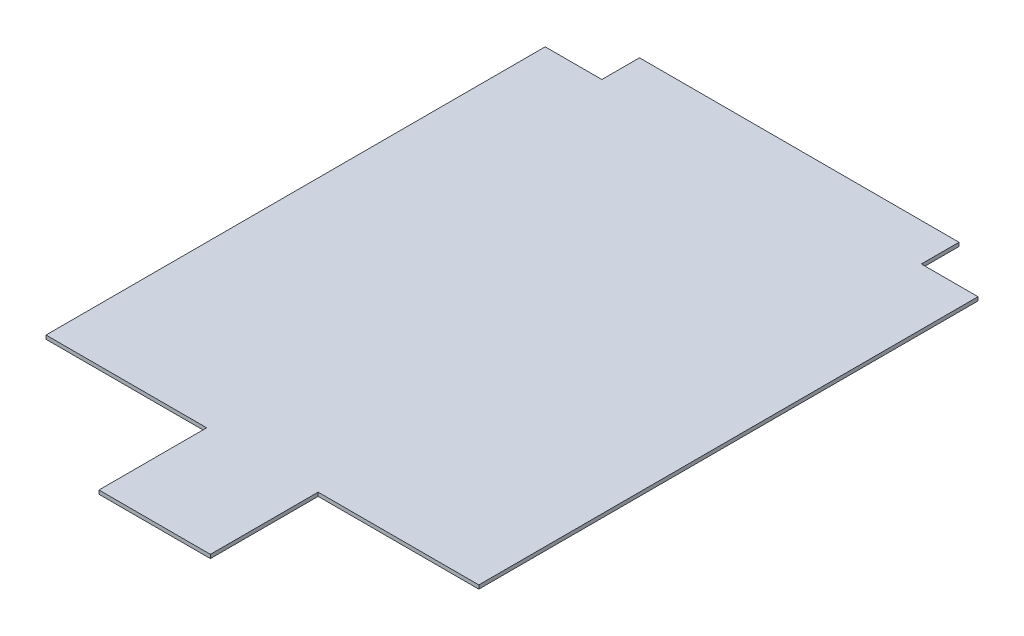
SolidWorks part; units mm, degrees
ref_plane "Plano frontal" through (0, 0, 0) normal (0, 0, 1) x (1, 0, 0)
ref_plane "Plano superior" through (0, 0, 0) normal (0, 1, 0) x (1, 0, 0)
ref_plane "Plano direito" through (0, 0, 0) normal (1, 0, 0) x (0, 0, -1)
sketch "Esboço1" plane through (0, 0, 0) normal (0, 1, 0) x (1, 0, 0)
  line L0 (36.5152, 74.051) -> (51.7652, 74.051)
  line L1 (-6.4848, 84.1831) -> (36.5152, 84.1831)
  line L2 (-6.4848, 84.1831) -> (-49.4848, 84.1831)
  line L3 (46.7652, 8.9331) -> (51.7652, 8.9331)
  line L4 (-6.4848, -89.3169) -> (8.5152, -89.3169)
  line L5 (-6.4848, -89.3169) -> (-21.4848, -89.3169)
  line L6 (-64.7348, 8.9331) -> (-64.7348, 74.051)
  line L7 (-64.7348, 8.9331) -> (-64.7348, -60.3184)
  line L8 (51.7652, 8.9331) -> (51.7652, 74.051)
  line L9 (51.7652, 8.9331) -> (51.7652, -60.3184)
  line L10 (8.5152, -69.8176) -> (8.5152, -60.3184)
  line L11 (-21.4848, -69.8176) -> (-21.4848, -60.3184)
  line L12 (8.5152, -60.3184) -> (51.7652, -60.3184)
  line L13 (-21.4848, -60.3184) -> (-64.7348, -60.3184)
  line L14 (-49.4848, 74.051) -> (-49.4848, 84.1831)
  line L15 (36.5152, 74.051) -> (36.5152, 84.1831)
  line L16 (-64.7348, 74.051) -> (-49.4848, 74.051)
  line L17 (-21.4848, -69.8176) -> (-21.4848, -89.3169)
  line L18 (8.5152, -69.8176) -> (8.5152, -89.3169)
extrude "Ressalto-extrusão1" add sketch "Esboço1" along normal mid plane 1
